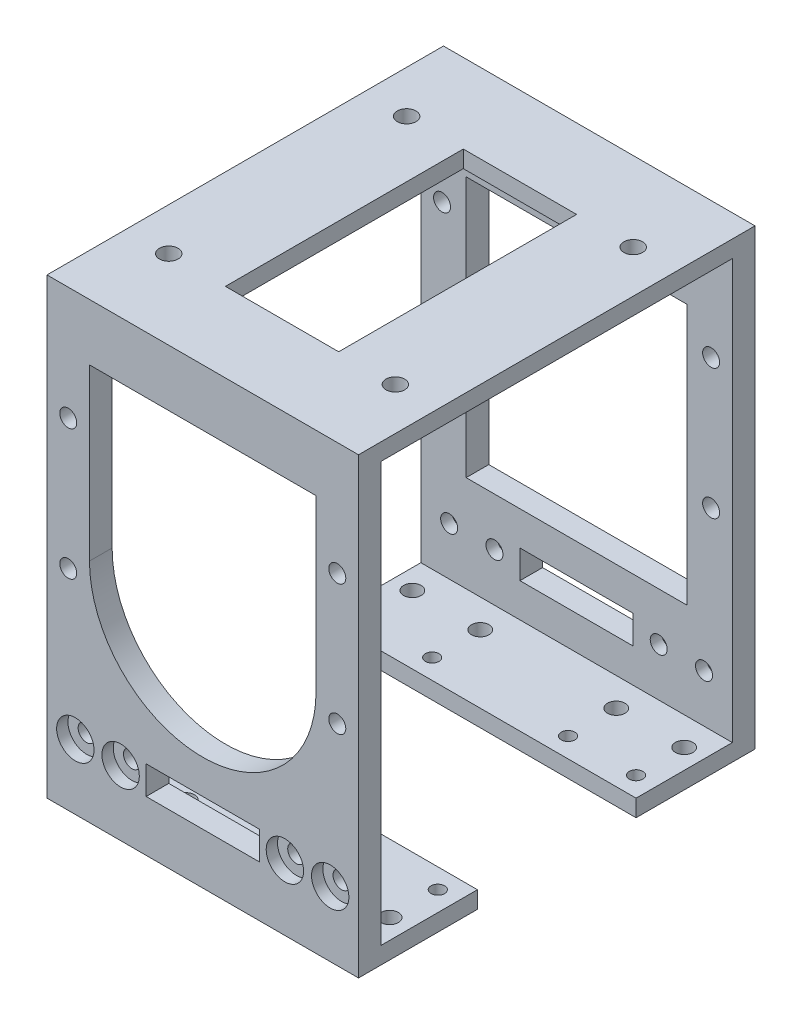
SolidWorks part; units mm, degrees
ref_plane "Front Plane" through (0, 0, 0) normal (0, 0, 1) x (1, 0, 0)
ref_plane "Top Plane" through (0, 0, 0) normal (0, 1, 0) x (1, 0, 0)
ref_plane "Right Plane" through (0, 0, 0) normal (1, 0, 0) x (0, 0, -1)
sketch "Sketch1" plane through (0, 0, 0) normal (0, 1, 0) x (1, 0, 0)
  line L0 (0, 0) -> (0, -14.43) construction
  line L1 (-37.5, 20) -> (37.5, 20)
  line L2 (-37.5, 20) -> (-37.5, -20)
  line L3 (-37.5, -20) -> (37.5, -20)
  line L4 (37.5, 20) -> (37.5, -20)
  line L5 (-37.5, 20) -> (37.5, -20) construction
  line L6 (-37.5, -20) -> (37.5, 20) construction
  line L7 (0, 0) -> (6.508, 0) construction
  line L8 (-5, 10) -> (5, 10)
  line L9 (-5, 10) -> (-5, -10)
  line L10 (-5, -10) -> (5, -10)
  line L11 (5, 10) -> (5, -10)
  line L12 (-5, 10) -> (5, -10) construction
  line L13 (-5, -10) -> (5, 10) construction
  circle A0 centre (-21, 0) radius 5
  circle A1 centre (-30, 8.25) radius 1.7
  circle A2 centre (-12, 8.25) radius 1.7
  circle A3 centre (-12, -8.25) radius 1.7
  circle A4 centre (-30, -8.25) radius 1.7
  circle A5 centre (12, 8.25) radius 1.7
  circle A6 centre (12, -8.25) radius 1.7
  circle A7 centre (21, 0) radius 5
  circle A8 centre (30, -8.25) radius 1.7
  circle A9 centre (30, 8.25) radius 1.7
  point P0 (0, 0)
  dimension "D3" = 10
  dimension "D4" = 16.5
  dimension "D5" = 16.5
  dimension "D6" = 18
  dimension "D9" = 10
  dimension "D11" = 20
  dimension "D13" = 7.5
  dimension "D17" = 3.4
  dimension "D19" = 11.75
  dimension "D20" = 11.75
  dimension "D1" = 75
  dimension "D2" = 40
  dimension "D10" = 10
  dimension "D7" = 2
  dimension "D8" = 2
extrude "Boss-Extrude1" add sketch "Sketch1" along normal blind 3
sketch "Sketch2" plane through (0, 3, 0) normal (0, 1, 0) x (1, 0, 0)
  line L0 (-37.5, 20) -> (-37.5, -20) construction
  line L1 (-33.5, 14) -> (33.5, 14)
  line L2 (-33.5, 14) -> (-33.5, -14)
  line L3 (-33.5, -14) -> (33.5, -14)
  line L4 (33.5, 14) -> (33.5, -14)
  line L5 (37.5, -20) -> (37.5, 20) construction
  line L6 (37.5, 20) -> (-37.5, 20) construction
  line L7 (-37.5, -20) -> (37.5, -20) construction
  dimension "D1" = 4
  dimension "D2" = 4
  dimension "D3" = 6
  dimension "D4" = 6
extrude "Cut-Extrude1" cut sketch "Sketch2" against normal through all both and the other way through all
sketch "Sketch3" plane through (0, 3, 0) normal (0, 1, 0) x (1, 0, 0)
  line L1 (37.5, 20) -> (-37.5, 20)
  line L2 (37.5, 20) -> (37.5, 35)
  line L3 (37.5, 35) -> (-37.5, 35)
  line L4 (-37.5, 20) -> (-37.5, 35)
  line L5 (-37.5, -20) -> (37.5, -20)
  line L6 (-37.5, -20) -> (-37.5, -35)
  line L7 (-37.5, -35) -> (37.5, -35)
  line L8 (37.5, -20) -> (37.5, -35)
  line L10 (-37.5, 20) -> (-33.5, 20)
  line L11 (-37.5, 20) -> (-37.5, -20)
  line L12 (-37.5, -20) -> (-33.5, -20)
  line L13 (-33.5, 20) -> (-33.5, -20)
  line L14 (37.5, 20) -> (33.5, 20)
  line L15 (37.5, 20) -> (37.5, -20)
  line L16 (37.5, -20) -> (33.5, -20)
  line L17 (33.5, 20) -> (33.5, -20)
  line M3 (-33.5, -14) -> (-33.5, 14)
  line M5 (33.5, 14) -> (33.5, -14)
  line M11 (37.5, -20) -> (37.5, 20)
  line M12 (37.5, 20) -> (-37.5, 20)
  line M13 (-37.5, 20) -> (-37.5, -20)
  line M14 (-37.5, -20) -> (37.5, -20)
  dimension "D1" = 15
  dimension "D2" = 15
extrude "Boss-Extrude3" add sketch "Sketch3" along normal blind 110 and the other way blind 3 contours L8 L5 L6 L7 M14 | L4 L1 L2 L3 M12 | L17 M12 M5 M14 M11 | L13 L1 M13 M14 M3
sketch "Sketch6" plane through (0, 3, 0) normal (0, 1, 0) x (1, 0, 0)
  line L0 (-37.5, -35) -> (37.5, -35) construction
  line L1 (-33.5, -20) -> (33.5, -20)
  line L2 (-33.5, -20) -> (-33.5, -31)
  line L3 (-33.5, -31) -> (33.5, -31)
  line L4 (33.5, -20) -> (33.5, -31)
  line L5 (33.5, 20) -> (-33.5, 20)
  line L6 (33.5, 20) -> (33.5, 31)
  line L7 (33.5, 31) -> (-33.5, 31)
  line L8 (-33.5, 20) -> (-33.5, 31)
  line L9 (37.5, 35) -> (-37.5, 35) construction
  dimension "D1" = 4
  dimension "D2" = 4
extrude "Cut-Extrude4" cut sketch "Sketch6" along normal through all
sketch "Sketch7" plane through (-37.5, 0, 0) normal (-1, 0, 0) x (0, 0, 1)
  line L0 (35, 0) -> (35, 113) construction
  line L1 (-35, 113) -> (35, 113)
  line L2 (-35, 113) -> (-35, 76)
  line L3 (-35, 76) -> (35, 76)
  line L4 (35, 113) -> (35, 76)
  dimension "D1" = 37
extrude "Boss-Extrude4" add sketch "Sketch7" along normal blind 45
ref_plane "Plane1" through (0, 0, 0) normal (1, 0, 0) x (0, 0, -1)
mirror "Mirror2" about plane through (0, 0, 0) normal (1, 0, 0) of "Boss-Extrude4"
sketch "Sketch8" plane through (0, 113, 0) normal (0, 1, 0) x (1, 0, 0)
  line L0 (-82.5, -35) -> (-82.5, 35) construction
  line L1 (-33.5, 31) -> (-78.5, 31)
  line L2 (-33.5, 31) -> (-33.5, -31)
  line L3 (-33.5, -31) -> (-78.5, -31)
  line L4 (-78.5, 31) -> (-78.5, -31)
  line L5 (33.5, -31) -> (78.5, -31)
  line L6 (33.5, -31) -> (33.5, 31)
  line L7 (33.5, 31) -> (78.5, 31)
  line L8 (78.5, -31) -> (78.5, 31)
  line L9 (82.5, -35) -> (82.5, 35) construction
  dimension "D1" = 4
  dimension "D2" = 4
extrude "Cut-Extrude6" cut sketch "Sketch8" against normal blind 29
sketch "Sketch9" plane through (-82.5, 0, 0) normal (-1, 0, 0) x (0, 0, 1)
  line L18 (-31, 84) -> (31, 84) construction
  line L19 (-19, 84) -> (19, 84)
  line L20 (-19, 84) -> (-19, 112.5)
  line L21 (-19, 112.5) -> (19, 112.5)
  line L22 (19, 84) -> (19, 112.5)
  line L25 (-31, 84) -> (-31, 113) construction
  dimension "D1" = 38
  dimension "D2" = 12
  dimension "D3" = 28.5
sketch "Sketch11" plane through (0, 0, 35) normal (0, 0, 1) x (1, 0, 0)
  line L0 (82.5, 76) -> (82.5, 113) construction
  line L1 (-82.5, 76) -> (-37.5, 76)
  line L2 (-82.5, 76) -> (-82.5, 80)
  line L3 (-82.5, 80) -> (-37.5, 80)
  line L4 (-37.5, 76) -> (-37.5, 80)
  line L5 (37.5, 76) -> (82.5, 76)
  line L6 (37.5, 76) -> (37.5, 80)
  line L7 (37.5, 80) -> (82.5, 80)
  line L8 (82.5, 76) -> (82.5, 80)
  line L11 (-78.5, 84) -> (-33.5, 84) construction
  line L12 (33.5, 84) -> (78.5, 84) construction
  dimension "D1" = 4
  dimension "D2" = 4
extrude "Cut-Extrude9" cut sketch "Sketch11" against normal through all
extrude "Cut-Extrude10" cut sketch "Sketch9" against normal through all
sketch "Sketch13" plane through (0, 84, 0) normal (0, 1, 0) x (1, 0, 0)
  line L0 (-78.5, 31) -> (-78.5, -31) construction
  line L1 (-57, 19) -> (-52, 19)
  line L2 (-57, 19) -> (-57, -19)
  line L3 (-57, -19) -> (-52, -19)
  line L4 (-52, 19) -> (-52, -19)
  line L7 (78.5, 31) -> (-78.5, 31) construction
  line L13 (-57, -19) -> (-57, 19)
  line L17 (-82.5, -19) -> (-107.5, -19)
  line L18 (-82.5, -19) -> (-82.5, 19)
  line L19 (-82.5, 19) -> (-107.5, 19)
  line L20 (-107.5, -19) -> (-107.5, 19)
  line L21 (-107.5, 19) -> (-61, 19)
  line L22 (-107.5, 19) -> (-107.5, -19)
  line L23 (-107.5, -19) -> (-61, -19)
  line L24 (-61, 19) -> (-61, -19)
  dimension "D1" = 21.5
  dimension "D2" = 5
  dimension "D3" = 38
  dimension "D4" = 12
  dimension "D5" = 25
  dimension "D6" = 46.5
extrude "Boss-Extrude5" add sketch "Sketch13" along normal blind 32 contours L4 L1 L2 L3
sketch "Sketch14" plane through (-57, 0, 0) normal (-1, 0, 0) x (0, 0, 1)
  line L0 (-19, 116) -> (-19, 84) construction
  line L4 (19, 112.5) -> (-19, 112.5) construction
  circle A0 centre (0, 98.25) radius 5
  circle A1 centre (-9, 106.5) radius 1.7
  circle A2 centre (9, 106.5) radius 1.7
  circle A3 centre (9, 90) radius 1.7
  circle A4 centre (-9, 90) radius 1.7
  dimension "D1" = 19
  dimension "D2" = 9
  dimension "D3" = 10
  dimension "D6" = 3.4
  dimension "D7" = 14.25
  dimension "D8" = 16.5
  dimension "D9" = 18
  dimension "D10" = 8.25
  dimension "D4" = 2
  dimension "D5" = 2
extrude "Cut-Extrude11" cut sketch "Sketch14" against normal blind 32
mirror "Mirror4" about plane through (0, 0, 0) normal (1, 0, 0) of "Boss-Extrude5", "Cut-Extrude11"
sketch "Sketch15" plane through (0, 113, 0) normal (0, 1, 0) x (1, 0, 0)
  line L1 (-82.5, 35) -> (82.5, 35)
  line L2 (-82.5, 35) -> (-82.5, -35)
  line L3 (-82.5, -35) -> (82.5, -35)
  line L4 (82.5, 35) -> (82.5, -35)
  line L5 (-78.5, 31) -> (78.5, 31)
  line L6 (-78.5, 31) -> (-78.5, -31)
  line L7 (-78.5, -31) -> (78.5, -31)
  line L8 (78.5, 31) -> (78.5, -31)
extrude "Boss-Extrude6" add sketch "Sketch15" along normal blind 3
sketch "Sketch16" plane through (0, 0, 35) normal (0, 0, 1) x (1, 0, 0)
  line L0 (-37.5, 0) -> (37.5, 0) construction
  line L1 (-10, 14) -> (10, 14)
  line L2 (-10, 14) -> (-10, 9)
  line L3 (-10, 9) -> (10, 9)
  line L4 (10, 14) -> (10, 9)
  line L5 (-37.5, 0) -> (-37.5, 80) construction
  dimension "D1" = 20
  dimension "D2" = 27.5
  dimension "D3" = 5
  dimension "D4" = 9
extrude "Cut-Extrude12" cut sketch "Sketch16" against normal through all
sketch "Sketch18" plane through (0, 0, 35) normal (0, 0, 1) x (1, 0, 0)
  line L0 (57, 116) -> (57, 84) construction
  line L2 (33.5, 84) -> (78.5, 84) construction
  circle A0 centre (67.75, 100) radius 5
  dimension "D1" = 10.75
  dimension "D2" = 16
  dimension "D3" = 10
extrude "Cut-Extrude14" cut sketch "Sketch18" against normal through all
mirror "Mirror5" about plane through (0, 0, 0) normal (1, 0, 0) of "Cut-Extrude14"
mirror "Mirror6" about plane through (0, 116, 0) normal (0, 1, 0) of "Mirror4", "Boss-Extrude5", "Cut-Extrude11"
sketch "Sketch19" plane through (82.5, 0, 0) normal (1, 0, 0) x (0, 0, -1)
  line L0 (19, 148) -> (19, 84) construction
  line L1 (-19, 112.5) -> (19, 112.5)
  line L2 (-19, 112.5) -> (-19, 116)
  line L3 (-19, 116) -> (19, 116)
  line L4 (19, 112.5) -> (19, 116)
extrude "Cut-Extrude15" cut sketch "Sketch19" against normal blind 10
mirror "Mirror7" about plane through (0, 0, 0) normal (1, 0, 0) of "Cut-Extrude15"
sketch "Sketch20" plane through (0, 3, 0) normal (0, 1, 0) x (1, 0, 0)
  line L0 (33.5, 31) -> (-33.5, 31) construction
  line L1 (-5, -10) -> (5, -10)
  line L2 (-5, -10) -> (-5, 10)
  line L3 (-5, 10) -> (5, 10)
  line L4 (5, -10) -> (5, 10)
  line L5 (-5, -10) -> (5, 10) construction
  line L6 (-5, 10) -> (5, -10) construction
  line L7 (0, 0) -> (0, 17.5) construction
  line L8 (-37.5, 20) -> (37.5, 20)
  line L9 (-37.5, 20) -> (-37.5, -20)
  line L10 (-37.5, -20) -> (37.5, -20)
  line L11 (37.5, 20) -> (37.5, -20)
  line L12 (-37.5, 20) -> (37.5, -20) construction
  line L13 (-37.5, -20) -> (37.5, 20) construction
  line L14 (0, -34.1) -> (0, 34.1) construction
  circle A1 centre (-12, 17.5) radius 1.2
  circle A2 centre (-12, -17.5) radius 1.2
  circle A3 centre (-24, -17.5) radius 1.2
  circle A4 centre (-24, 17.5) radius 1.2
  circle A5 centre (12, -17.5) radius 1.2
  circle A6 centre (24, -17.5) radius 1.2
  circle A7 centre (12, 17.5) radius 1.2
  circle A8 centre (24, 17.5) radius 1.2
  point P2 (0, 0)
  point P10 (0, 0)
  dimension "D1" = 7
  dimension "D2" = 10
  dimension "D4" = 2.5
  dimension "D7" = 35
  dimension "D8" = 7
  dimension "D9" = 2.4
  dimension "D11" = 12
  dimension "D3" = 21
  dimension "D5" = 75
  dimension "D6" = 40
  dimension "D10" = 2
extrude "Cut-Extrude16" cut sketch "Sketch20" against normal blind 10 contours A4 | A1 | A7 | A3 | A2 | A8 | A5 | A6
sketch "Sketch21" plane through (0, 0, 35) normal (0, 0, 1) x (1, 0, 0)
  line L0 (0, -34.1) -> (0, 34.1) construction
  line L1 (37.5, 0) -> (27.5, 0)
  line L2 (37.5, 0) -> (37.5, 80)
  line L3 (37.5, 80) -> (27.5, 80)
  line L4 (27.5, 0) -> (27.5, 80)
  line L5 (-27.5, 0) -> (-27.5, 80)
  line L6 (-37.5, 80) -> (-27.5, 80)
  line L7 (-37.5, 0) -> (-37.5, 80)
  line L8 (-37.5, 0) -> (-27.5, 0)
  dimension "D1" = 10
  dimension "D2" = 80
extrude "Cut-Extrude17" cut sketch "Sketch21" against normal through all
sketch "Sketch22" plane through (0, 0, 35) normal (0, 0, 1) x (1, 0, 0)
  line L1 (82.5, 80) -> (-90.2391, 80)
  line L2 (82.5, 80) -> (82.5, 155.8432)
  line L3 (82.5, 155.8432) -> (-90.2391, 155.8432)
  line L4 (-90.2391, 80) -> (-90.2391, 155.8432)
extrude "Cut-Extrude18" cut sketch "Sketch22" against normal through all
sketch "Sketch23" plane through (0, 80, 0) normal (0, 1, 0) x (1, 0, 0)
  line L5 (-27.5, 35) -> (27.5, 35)
  line L6 (-27.5, 35) -> (-27.5, -35)
  line L7 (-27.5, -35) -> (27.5, -35)
  line L8 (27.5, 35) -> (27.5, -35)
extrude "Boss-Extrude7" add sketch "Sketch23" against normal blind 3
sketch "Sketch24" plane through (0, 80, 0) normal (0, 1, 0) x (1, 0, 0)
  line L0 (-27.5, 35) -> (27.5, 35) construction
  line L1 (-27.5, 35) -> (-27.5, -35) construction
  line L2 (0, -34.1) -> (0, 34.1) construction
  circle A0 centre (0, 0) radius 10
  circle A1 centre (-20, 21) radius 1.65
  circle A2 centre (-20, -21) radius 1.65
  circle A3 centre (20, -21) radius 1.65
  circle A4 centre (20, 21) radius 1.65
  point P0 (0, 0)
  dimension "D2" = 35
  dimension "D1" = 21
  dimension "D3" = 27.5
  dimension "D4" = 20
  dimension "D5" = 3.3
  dimension "D6" = 3.3
  dimension "D7" = 21
  dimension "D8" = 20
extrude "Cut-Extrude19" cut sketch "Sketch24" against normal blind 3
sketch "Sketch25" plane through (0, 0, 0) normal (0, -1, 0) x (1, 0, 0)
  line L0 (-27.5, 35) -> (27.5, 35) construction
  line L2 (-27.5, 14) -> (-27.5, 35) construction
  line L3 (0, 0) -> (35.9025, 0) construction
  line L4 (0, 0) -> (0, -14.2045) construction
  line L5 (0, -55) -> (0, 55) construction
  circle A0 centre (-24, 26) radius 1.55
  circle A1 centre (12, -26) radius 1.55
  circle A2 centre (24, -26) radius 1.55
  circle A4 centre (12, 26) radius 1.55
  circle A5 centre (-12, 26) radius 1.55
  circle A6 centre (-24, -26) radius 1.55
  circle A7 centre (-12, -26) radius 1.55
  circle A8 centre (24, 26) radius 1.55
  dimension "D1" = 3.1
  dimension "D2" = 3.5
  dimension "D3" = 2
  dimension "D4" = 9
  dimension "D5" = 12
extrude "Cut-Extrude20" cut sketch "Sketch25" against normal blind 10
sketch "Sketch27" plane through (0, 0, -35) normal (0, 0, -1) x (-1, 0, 0)
  line L0 (27.5, 80) -> (-27.5, 80) construction
  line L1 (-19.5, 66) -> (19.5, 66)
  line L2 (-19.5, 66) -> (-19.5, 20)
  line L3 (-19.5, 20) -> (19.5, 20)
  line L4 (19.5, 66) -> (19.5, 20)
  line L5 (27.5, 0) -> (27.5, 80) construction
  line L6 (-27.5, 80) -> (-27.5, 0) construction
  line L7 (-27.5, 0) -> (27.5, 0) construction
  dimension "D1" = 14
  dimension "D2" = 8
  dimension "D3" = 8
  dimension "D4" = 20
extrude "Cut-Extrude21" cut sketch "Sketch27" against normal blind 4
sketch "Sketch29" plane through (0, 80, 0) normal (0, 1, 0) x (1, 0, 0)
  line L1 (-10, 21) -> (10, 21)
  line L2 (-10, 21) -> (-10, -21)
  line L3 (-10, -21) -> (10, -21)
  line L4 (10, 21) -> (10, -21)
  line L5 (-10, 21) -> (10, -21) construction
  line L6 (-10, -21) -> (10, 21) construction
  point P0 (0, 0)
  dimension "D1" = 20
  dimension "D2" = 42
extrude "Cut-Extrude22" cut sketch "Sketch29" against normal blind 10
sketch "Sketch31" plane through (0, 0, -35) normal (0, 0, -1) x (-1, 0, 0)
  line L0 (27.5, 0) -> (27.5, 80) construction
  line L1 (-27.5, 0) -> (27.5, 0) construction
  line L2 (0, 55) -> (0, -55) construction
  circle A0 centre (22.5, 11.5) radius 1.5
  circle A1 centre (14.5, 11.5) radius 1.5
  circle A2 centre (-14.5, 11.5) radius 1.5
  circle A3 centre (-22.5, 11.5) radius 1.5
  dimension "D1" = 3
  dimension "D2" = 5
  dimension "D3" = 11.5
  dimension "D5" = 8
  dimension "D4" = 2
extrude "Cut-Extrude23" cut sketch "Sketch31" against normal through all
ref_plane "Plane2" through (0, 0, 0) normal (0, 0, -1) x (-1, 0, 0)
sketch "Sketch32" plane through (0, 0, -35) normal (0, 0, -1) x (-1, 0, 0)
  line L0 (0, 55) -> (0, -55) construction
  circle A0 centre (-22.5, 11.5) radius 3.3
  circle A1 centre (-14.5, 11.5) radius 3.3
  circle A2 centre (14.5, 11.5) radius 3.3
  circle A3 centre (22.5, 11.5) radius 3.3
  dimension "D1" = 2
extrude "Cut-Extrude24" cut sketch "Sketch32" against normal blind 2
mirror "Mirror8" about plane through (0, 0, 0) normal (0, 0, -1) of "Cut-Extrude24"
sketch "Sketch33" plane through (0, 0, 35) normal (0, 0, 1) x (1, 0, 0)
  line L0 (-27.5, 80) -> (27.5, 80) construction
  line L1 (27.5, 80) -> (0, 80) construction
  line L2 (0, 80) -> (0, 0) construction
  line L5 (-20, 40) -> (20, 40)
  line L6 (-20, 40) -> (-20, 70)
  line L7 (-20, 70) -> (20, 70)
  line L8 (20, 40) -> (20, 70)
  circle A0 centre (0, 40) radius 20
  dimension "D1" = 40
  dimension "D2" = 10
extrude "Cut-Extrude25" cut sketch "Sketch33" against normal blind 10 contours A0 L8 L7 L6 | L5 A0 | L5 A0
sketch "Sketch34" plane through (0, 0, 35) normal (0, 0, 1) x (1, 0, 0)
  line L0 (-27.5, 0) -> (27.5, 0) construction
  line L1 (-27.5, 0) -> (-27.5, 80) construction
  line L3 (0, -55) -> (0, 55) construction
  circle A0 centre (-23.75, 60) radius 1.5
  circle A1 centre (23.75, 60) radius 1.5
  circle A2 centre (-23.75, 37) radius 1.5
  circle A3 centre (23.75, 37) radius 1.5
  dimension "D1" = 3
  dimension "D2" = 60
  dimension "D3" = 3.75
  dimension "D5" = 23
  dimension "D4" = 2
extrude "Cut-Extrude26" cut sketch "Sketch34" against normal through all
